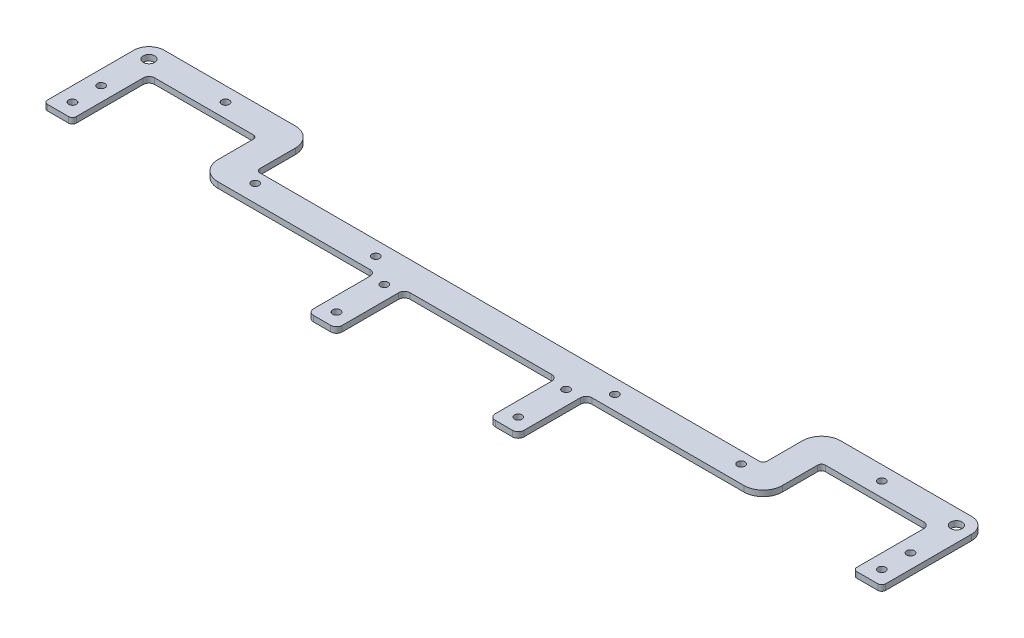
SolidWorks part; units mm, degrees
material "Thornel Mat VMA"
ref_plane "前视基准面" through (0, 0, 0) normal (0, 0, 1) x (1, 0, 0)
ref_plane "上视基准面" through (0, 0, 0) normal (0, 1, 0) x (1, 0, 0)
ref_plane "右视基准面" through (0, 0, 0) normal (1, 0, 0) x (0, 0, -1)
sketch "草图1" plane through (0, 0, 0) normal (0, 1, 0) x (1, 0, 0)
  line L1 (-55, 0) -> (55, 0)
  line L12 (-204, 66) -> (-147.5, 66)
  line L28 (-211, 81) -> (-132.5, 81)
  line L31 (-147.5, 66) -> (-147.5, 35.5)
  line L37 (-219, 73) -> (-219, 26)
  line L39 (0, 0) -> (0, 41) construction
  line L41 (219, 73) -> (219, 26)
  line L43 (147.5, 66) -> (147.5, 35.5)
  line L47 (204, 66) -> (147.5, 66)
  line L66 (-219, 26) -> (-204, 26)
  line L67 (219, 26) -> (204, 26)
  line L68 (-204, 26) -> (-204, 66)
  line L69 (204, 26) -> (204, 66)
  line L70 (-55, 0) -> (-55, 35.5)
  line L71 (55, 0) -> (55, 35.5)
  line L80 (-147.5, 35.5) -> (-55, 35.5)
  line L81 (147.5, 35.5) -> (55, 35.5)
  line L87 (0, -1.65) -> (0, 1.65) construction
  line L91 (-132.5, 81) -> (-132.5, 50.5)
  line L92 (-132.5, 50.5) -> (132.5, 50.5)
  line L93 (132.5, 81) -> (132.5, 50.5)
  line L94 (211, 81) -> (132.5, 81)
  arc A3 (-219, 73) -> (-211, 81) centre (-211, 73) cw
  arc A4 (219, 73) -> (211, 81) centre (211, 73) ccw
  dimension "D3" = 81
  dimension "D4" = 35.5
  dimension "D5" = 132.5
  dimension "D6" = 15
  dimension "D7" = 8
  dimension "D9" = 15
  dimension "D10" = 15
  dimension "D15" = 110
  dimension "D17" = 55
  dimension "D21" = 438
  dimension "D22" = 15
extrude "凸台-拉伸1" add sketch "草图1" along normal blind 3
sketch "草图2" plane through (0, 3, 0) normal (0, 1, 0) x (1, 0, 0)
  line L0 (55, 0) -> (55, 35.5) construction
  line L1 (-47.5, 7.5) -> (-47.5, 32.5) construction
  line L6 (-55, 0) -> (55, 0) construction
  line L7 (-219, 26) -> (-204, 26) construction
  line L8 (-55, 35.5) -> (-55, 0) construction
  line L11 (-132.5, 50.5) -> (-132.5, 81) construction
  line L14 (0, -1.65) -> (0, 1.65) construction
  line L15 (-40, 0) -> (40, 0)
  line L16 (0, 0) -> (0, 35.5) construction
  line L17 (-40, 0) -> (-40, 35.5)
  line L18 (-40, 35.5) -> (40, 35.5)
  line L19 (40, 0) -> (40, 35.5)
  line L20 (-147.5, 35.5) -> (-55, 35.5) construction
  line L21 (-55, 35.5) -> (-55, 0) construction
  line L22 (-204, 66) -> (-147.5, 66) construction
  line L23 (-219, 73) -> (-219, 26) construction
  line L26 (-55, 35.5) -> (-55, 0) construction
  line L27 (-55, 0) -> (55, 0) construction
  line L29 (132.5, 50.5) -> (-132.5, 50.5) construction
  circle A10 centre (-47.5, 32.5) radius 2
  circle A18 centre (-211.5, 33.5) radius 2
  circle A19 centre (-211.5, 48.5) radius 2
  circle A36 centre (211.5, 48.5) radius 2
  circle A37 centre (211.5, 33.5) radius 2
  circle A39 centre (-171.5, 73.5) radius 2
  circle A40 centre (171.5, 73.5) radius 2
  circle A45 centre (47.5, 32.5) radius 2
  circle A46 centre (-47.5, 7.5) radius 2
  circle A47 centre (-62.5, 43) radius 2
  circle A48 centre (-127, 44.5) radius 2
  circle A49 centre (62.5, 43) radius 2
  circle A50 centre (127, 44.5) radius 2
  circle A51 centre (47.5, 7.5) radius 2
  point P29 (-211.5, 26)
  dimension "D2" = 5.5
  dimension "D3" = 7.5
  dimension "D4" = 25
  dimension "D7" = 15
  dimension "D8" = 6
  dimension "D9" = 4
  dimension "D10" = 15
  dimension "D6" = 7.5
  dimension "D13" = 4
  dimension "D14" = 4
  dimension "D12" = 7.5
  dimension "D15" = 7.5
  dimension "D16" = 7.5
  dimension "D17" = 47.5
  dimension "D5" = 7.5
  dimension "D18" = 15
extrude "切除-拉伸1" cut sketch "草图2" against normal blind 10
sketch "草图5" plane through (0, 3, 0) normal (0, 1, 0) x (1, 0, 0)
  line L0 (0, -1.65) -> (0, 1.65) construction
  line L26 (-219, 73) -> (-219, 26) construction
  line L29 (-132.5, 81) -> (-211, 81) construction
  circle A16 centre (-211, 73) radius 3
  circle A19 centre (211, 73) radius 3
  dimension "D12" = 6
  dimension "D13" = 8
  dimension "D14" = 8
extrude "切除-拉伸4" cut sketch "草图5" against normal through all
fillet "圆角1" radius 10 4 edges at (-147.5, 1.5, -35.5) (147.5, 1.5, -35.5) (132.5, 1.5, -81) (-132.5, 1.5, -81)
fillet "圆角2" radius 3 10 edges at (40, 1.5, -35.5) (55, 1.5, 0) (40, 1.5, 0) (-55, 1.5, 0) (-40, 1.5, 0) (-40, 1.5, -35.5) (-55, 1.5, -35.5) (55, 1.5, -35.5) (204, 1.5, -66) (-204, 1.5, -66)
chamfer "倒角1" [suppressed] distance 2.5 distance2 2
chamfer "倒角2" [suppressed] distance 7.5 distance2 12
chamfer "倒角3" [suppressed] distance 12 distance2 7.5
fillet "圆角3" radius 2 8 edges at (-132.5, 1.5, -50.5) (-147.5, 1.5, -66) (-204, 1.5, -26) (-219, 1.5, -26) (219, 1.5, -26) (204, 1.5, -26) (147.5, 1.5, -66) (132.5, 1.5, -50.5)
